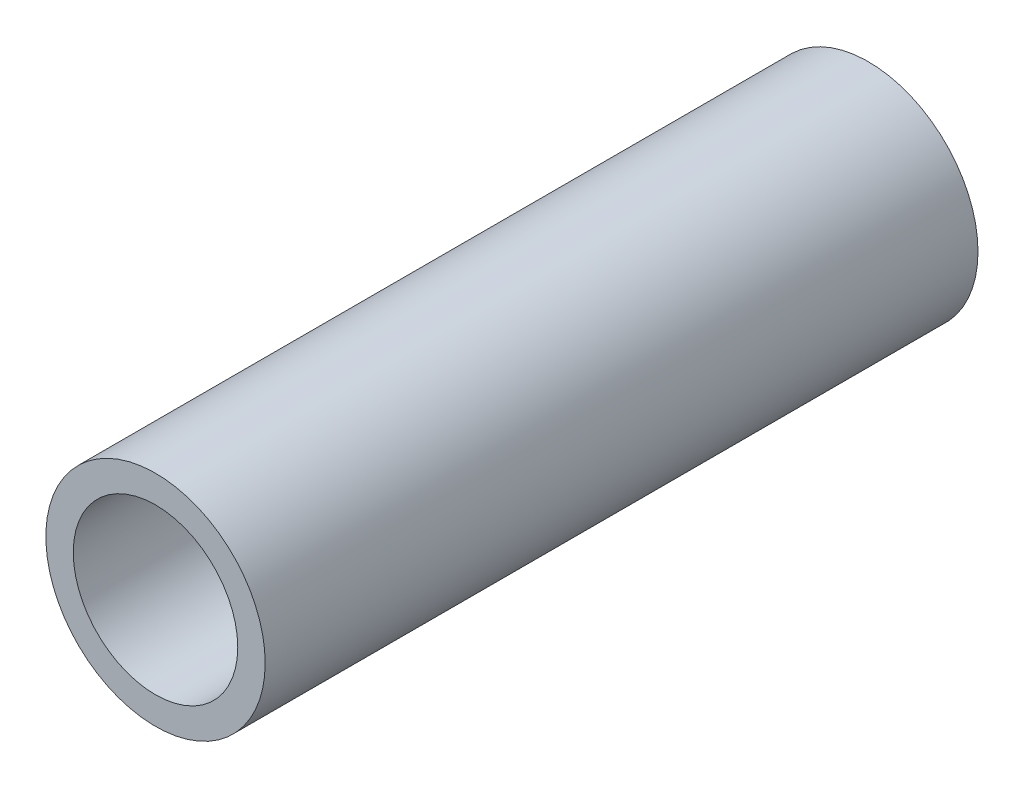
SolidWorks part; units mm, degrees
ref_plane "Front Plane" through (0, 0, 0) normal (0, 0, 1) x (1, 0, 0)
ref_plane "Top Plane" through (0, 0, 0) normal (0, 1, 0) x (1, 0, 0)
ref_plane "Right Plane" through (0, 0, 0) normal (1, 0, 0) x (0, 0, -1)
sketch "Sketch1" plane through (0, 0, 0) normal (0, 0, 1) x (1, 0, 0)
  circle A0 centre (0, 0) radius 20
  dimension "D1" = 40
extrude "Boss-Extrude1" add sketch "Sketch1" along normal blind 130
sketch "Sketch2" plane through (0, 0, 130) normal (0, 0, 1) x (1, 0, 0)
  circle A0 centre (0, 0) radius 15
  dimension "D1" = 30
extrude "Cut-Extrude1" cut sketch "Sketch2" against normal blind 130
